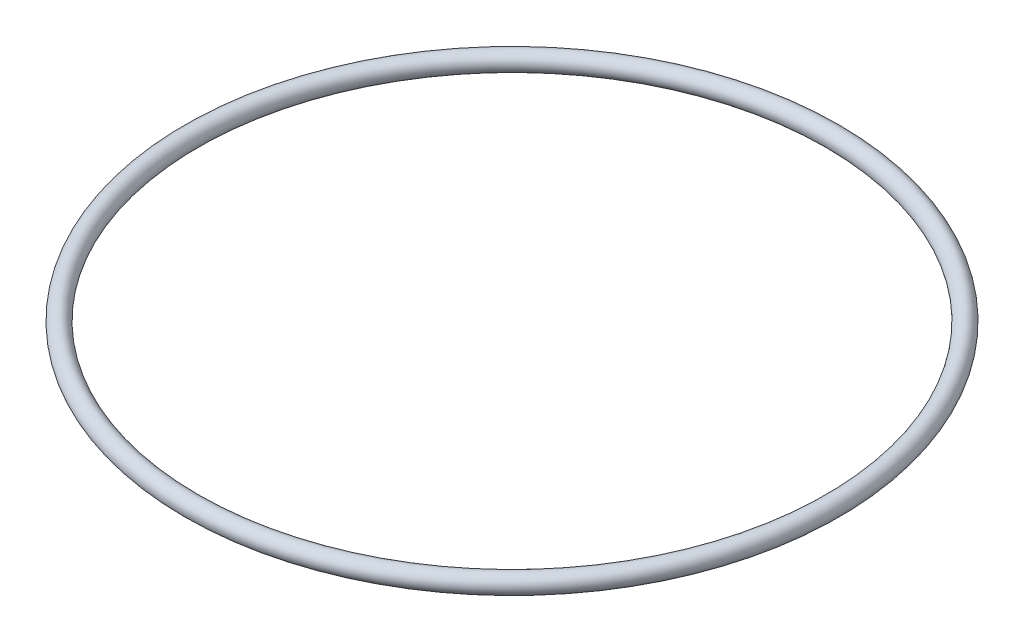
SolidWorks part; units mm, degrees
material "VITON"
ref_plane "Front Plane" through (0, 0, 0) normal (0, 0, 1) x (1, 0, 0)
ref_plane "Top Plane" through (0, 0, 0) normal (0, 1, 0) x (1, 0, 0)
ref_plane "Right Plane" through (0, 0, 0) normal (1, 0, 0) x (0, 0, -1)
sketch "Sketch1" plane through (0, 0, 0) normal (0, 0, 1) x (1, 0, 0)
  line L0 (0, 0) -> (0, 6.5809) construction
  circle A0 centre (-43.4, 0) radius 1.25
  dimension "D1" = 2.5
  dimension "D2" = 43.4
revolve "Revolve1" add sketch "Sketch1" angle 360 about L0
